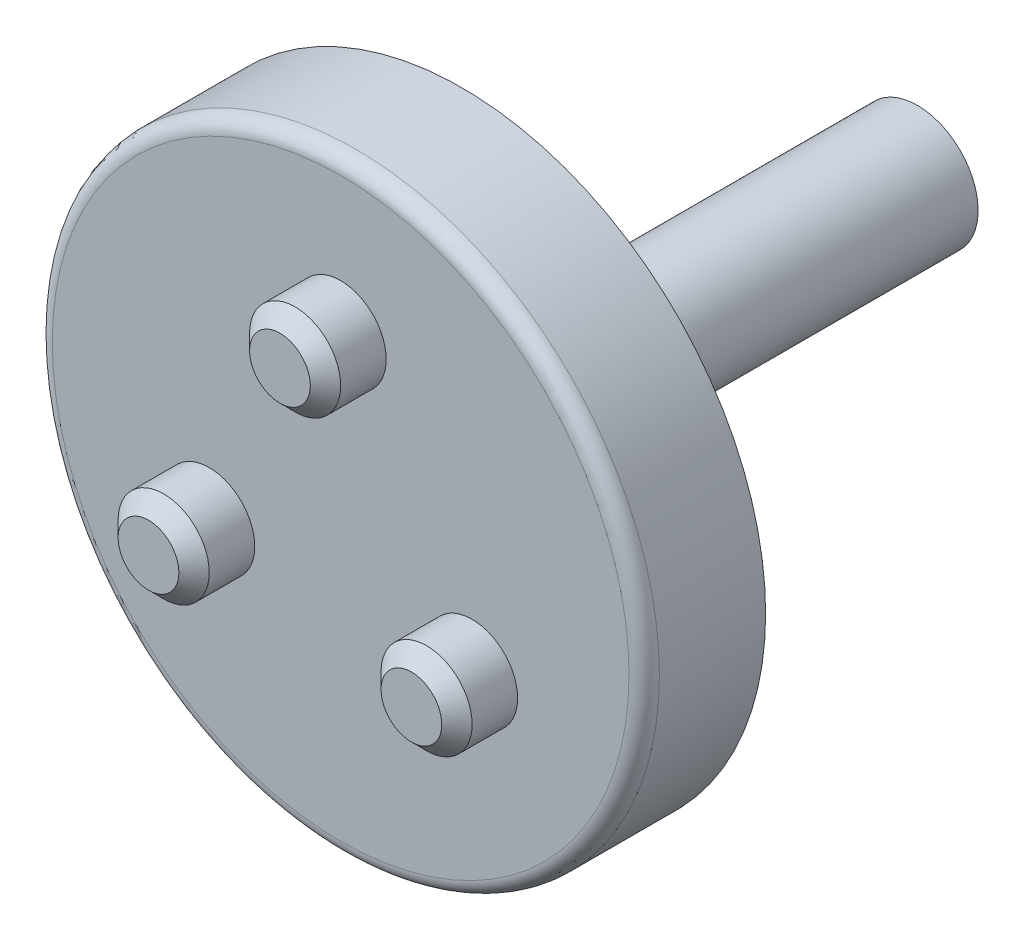
SolidWorks part; units mm, degrees
ref_plane "Front Plane" through (0, 0, 0) normal (0, 0, 1) x (1, 0, 0)
ref_plane "Top Plane" through (0, 0, 0) normal (0, 1, 0) x (1, 0, 0)
ref_plane "Right Plane" through (0, 0, 0) normal (1, 0, 0) x (0, 0, -1)
sketch "Sketch1" plane through (0, 0, 0) normal (0, 0, 1) x (1, 0, 0)
  circle A0 centre (0, 0) radius 100
  dimension "D1" = 200
extrude "Boss-Extrude1" add sketch "Sketch1" along normal blind 40
sketch "Sketch2" plane through (0, 0, 40) normal (0, 0, 1) x (1, 0, 0)
  line L0 (-100, 0) -> (100, 0) construction
  line L1 (0, 100) -> (0, -100) construction
  line L2 (0, 0) -> (0, 50) construction
  circle A0 centre (0, 0) radius 100 construction
  circle A1 centre (0, 50) radius 15
  circle A2 centre (0, 0) radius 50 construction
  circle A3 centre (43.3013, -25) radius 15
  circle A4 centre (-43.3013, -25) radius 15
  point P6 (0, 0)
  point P11 (0, 0)
  dimension "D1" = 30
  dimension "D3" = 3
  dimension "D2" = 50
  dimension "D4" = 50
extrude "Boss-Extrude2" add sketch "Sketch2" along normal blind 20
sketch "Sketch3" plane through (0, 0, 0) normal (0, 0, -1) x (-1, 0, 0)
  circle A0 centre (0, 0) radius 20
  dimension "D1" = 40
extrude "Boss-Extrude3" add sketch "Sketch3" along normal blind 150 separate body
chamfer "Chamfer1" distance 5 angle 45 3 edges at (-28.3013, -25, 60) (58.3013, -25, 60) (15, 50, 60)
fillet "Fillet1" radius 5 1 edges at (100, 0, 40)
sketch "Sketch5" plane through (0, 0, -150) normal (0, 0, -1) x (-1, 0, 0)
  circle A0 centre (0, 0) radius 20
  circle A1 centre (0, 0) radius 20 construction
